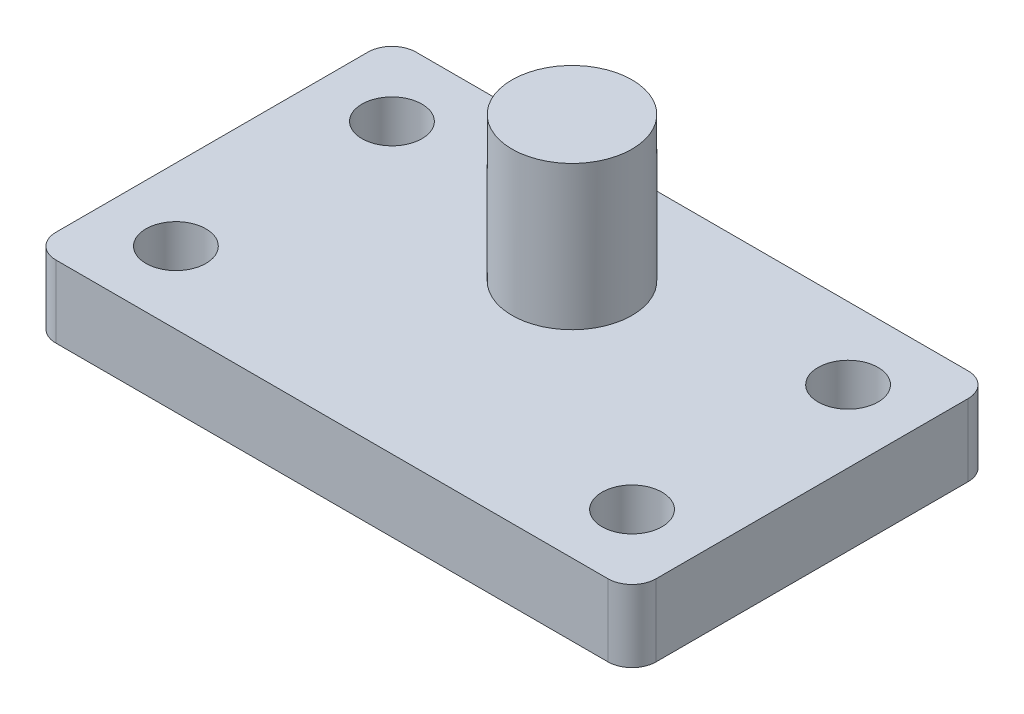
SolidWorks part; units mm, degrees
ref_plane "Ön Düzlem" through (0, 0, 0) normal (0, 0, 1) x (1, 0, 0)
ref_plane "Üst Düzlem" through (0, 0, 0) normal (0, 1, 0) x (1, 0, 0)
ref_plane "Sağ Düzlem" through (0, 0, 0) normal (1, 0, 0) x (0, 0, -1)
sketch "Çizim1" plane through (0, 0, 0) normal (0, 1, 0) x (1, 0, 0)
  line L1 (-115, 75) -> (115, 75)
  line L2 (-125, 65) -> (-125, -65)
  line L3 (-115, -75) -> (115, -75)
  line L4 (125, 65) -> (125, -65)
  line L5 (-125, 75) -> (125, -75) construction
  line L6 (-125, -75) -> (125, 75) construction
  arc A0 (115, 75) -> (125, 65) centre (115, 65) cw
  arc A1 (-125, -65) -> (-115, -75) centre (-115, -65) ccw
  arc A2 (-115, 75) -> (-125, 65) centre (-115, 65) ccw
  arc A3 (115, -75) -> (125, -65) centre (115, -65) ccw
  point P0 (0, 0)
  dimension "D3" = 10
  dimension "D1" = 150
  dimension "D2" = 250
extrude "Yükseklik-Ekstrüzyon1" add sketch "Çizim1" against normal blind 30
sketch "Çizim2" plane through (0, 0, 0) normal (0, 1, 0) x (1, 0, 0)
  line L0 (115, 75) -> (-115, 75) construction
  circle A0 centre (0, 25) radius 25
  point P4 (0, 0)
  dimension "D1" = 50
  dimension "D2" = 50
extrude "Yükseklik-Ekstrüzyon2" add sketch "Çizim2" along normal blind 60
sketch "Çizim3" plane through (0, 0, 0) normal (0, 1, 0) x (1, 0, 0)
  line L0 (115, 75) -> (-115, 75) construction
  line L1 (-125, 65) -> (-125, -65) construction
  circle A0 centre (-95, 45) radius 12.5
  dimension "D1" = 25
  dimension "D2" = 30
  dimension "D3" = 30
extrude "Kes-Ekstrüzyon1" cut sketch "Çizim3" against normal through all
pattern_linear "LÇoğaltma2" count 2 spacing 190 along (1, 0, 0) count 2 spacing 90 along (0, 0, 1) of "Kes-Ekstrüzyon1"
